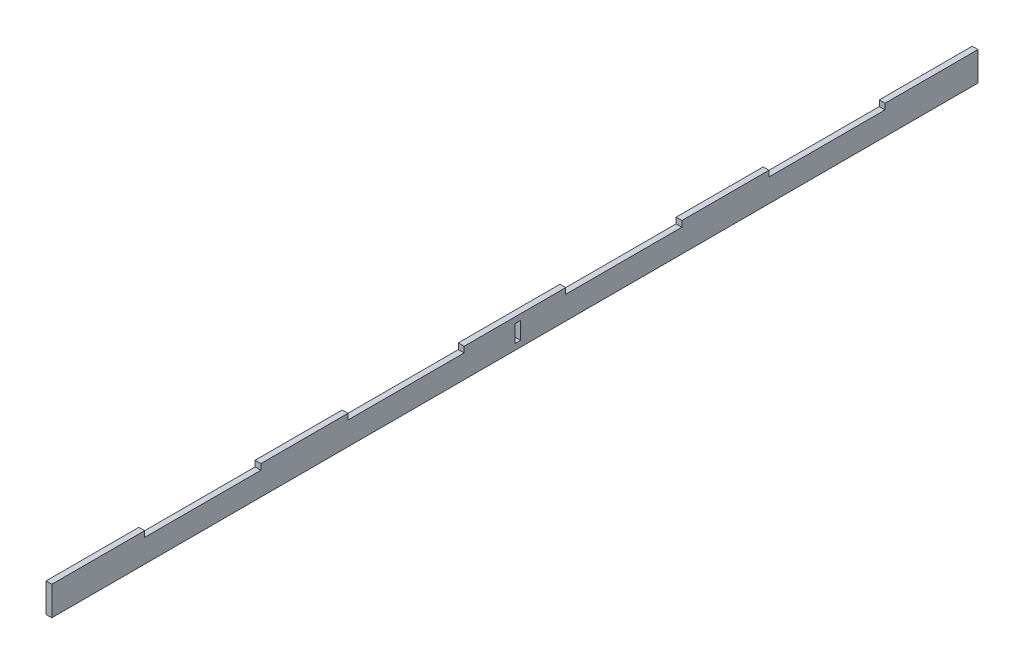
SolidWorks part; units mm, degrees
material "ABS PC"
ref_plane "Front Plane" through (0, 0, 0) normal (0, 0, 1) x (1, 0, 0)
ref_plane "Top Plane" through (0, 0, 0) normal (0, 1, 0) x (1, 0, 0)
ref_plane "Right Plane" through (0, 0, 0) normal (1, 0, 0) x (0, 0, -1)
sketch "Sketch1" plane through (0, 0, 0) normal (1, 0, 0) x (0, 0, -1)
  line L1 (-159.5, -5) -> (159.5, -5)
  line L2 (-159.5, -5) -> (-159.5, 5)
  line L3 (-159.5, 5) -> (159.5, 5)
  line L4 (159.5, -5) -> (159.5, 5)
  line L5 (-159.5, -5) -> (159.5, 5) construction
  line L6 (-159.5, 5) -> (159.5, -5) construction
  point P0 (0, 0)
  dimension "D1" = 10
  dimension "D2" = 319
extrude "Boss-Extrude1" add sketch "Sketch1" along normal blind 2
sketch "Sketch2" plane through (2, 0, 0) normal (1, 0, 0) x (0, 0, -1)
  line L0 (159.5, 5) -> (-159.5, 5) construction
  line L1 (-127.5, 5) -> (-87.5, 5)
  line L2 (-127.5, 5) -> (-127.5, 3)
  line L3 (-127.5, 3) -> (-87.5, 3)
  line L4 (-87.5, 5) -> (-87.5, 3)
  line L5 (-159.5, 5) -> (-159.5, -5) construction
  line L6 (-57.5, 5) -> (-17.5, 5)
  line L7 (-57.5, 5) -> (-57.5, 3)
  line L8 (-57.5, 3) -> (-17.5, 3)
  line L9 (-17.5, 5) -> (-17.5, 3)
  line L10 (0, 5.2414) -> (0, -5.2414) construction
  line L11 (17.5, 5) -> (17.5, 3)
  line L12 (57.5, 5) -> (17.5, 5)
  line L13 (57.5, 5) -> (57.5, 3)
  line L14 (57.5, 3) -> (17.5, 3)
  line L15 (127.5, 5) -> (127.5, 3)
  line L16 (127.5, 5) -> (87.5, 5)
  line L17 (87.5, 5) -> (87.5, 3)
  line L18 (127.5, 3) -> (87.5, 3)
  dimension "D1" = 32
  dimension "D2" = 2
  dimension "D3" = 40
  dimension "D4" = 30
  dimension "D5" = 40
  dimension "D6" = 2
extrude "Cut-Extrude1" cut sketch "Sketch2" against normal through all both and the other way through all
sketch "Sketch3" plane through (0, 0, 0) normal (0, 0, 1) x (1, 0, 0)
  line L1 (2, -5) -> (16, -7)
  line L2 (2, 5) -> (2, -5)
  line L3 (17, 0.855) -> (2, 5)
  arc A1 (17, 0.855) -> (16, -7) centre (15.9346, -3.0005) cw
  circle A2 centre (15.9346, -3.0005) radius 2
  dimension "D5" = 4
  dimension "D6" = 4
  dimension "D1" = 15
  dimension "D2" = 14
  dimension "D4" = 2
extrude "Boss-Extrude2" [suppressed] add sketch "Sketch3" along normal mid plane 1
sketch "Sketch4" plane through (2, 0, 0) normal (1, 0, 0) x (0, 0, -1)
  line L1 (0, 3) -> (2, 3)
  line L2 (0, 3) -> (0, -3)
  line L3 (0, -3) -> (2, -3)
  line L4 (2, 3) -> (2, -3)
  dimension "D1" = 2
  dimension "D2" = 6
  dimension "D3" = 3
  dimension "D4" = 2
extrude "Cut-Extrude2" cut sketch "Sketch4" against normal through all both and the other way through all
